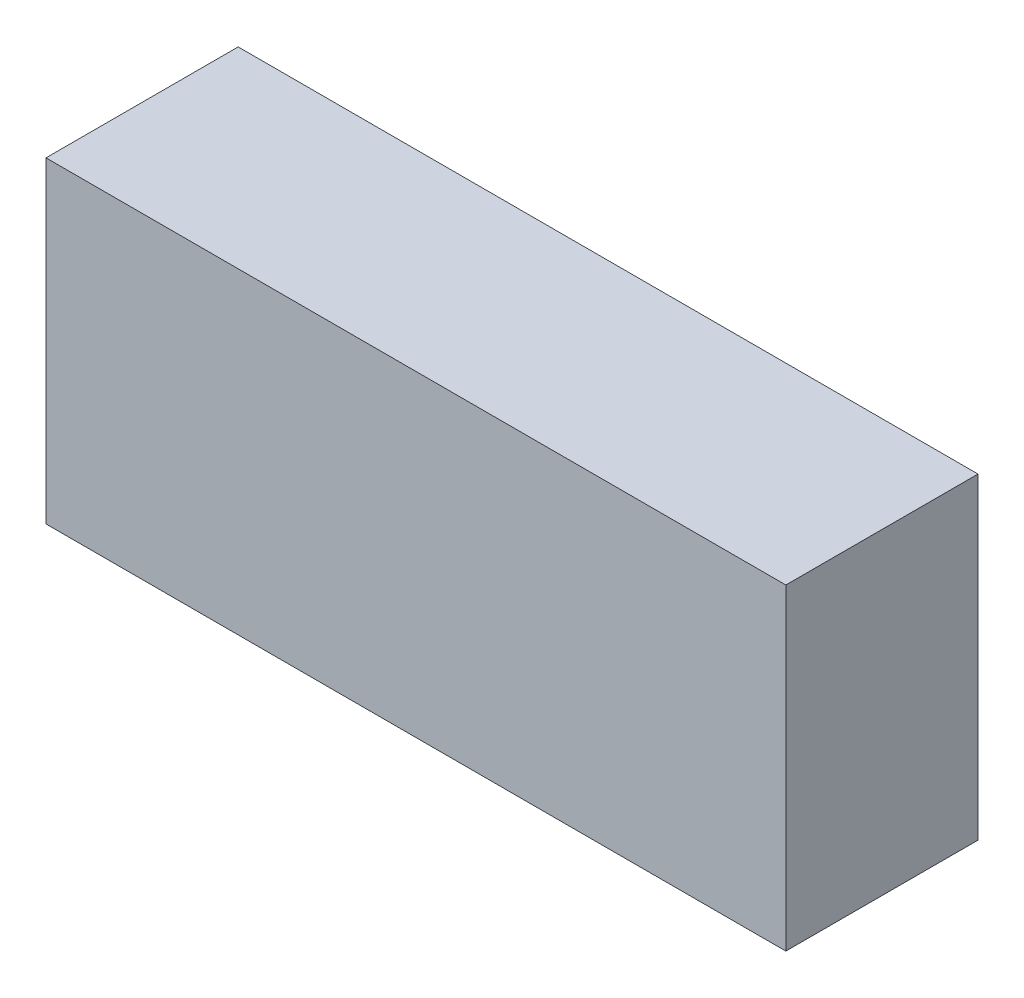
SolidWorks part; units mm, degrees
ref_plane "Plan de face" through (0, 0, 0) normal (0, 0, 1) x (1, 0, 0)
ref_plane "Plan de dessus" through (0, 0, 0) normal (0, 1, 0) x (1, 0, 0)
ref_plane "Plan de droite" through (0, 0, 0) normal (1, 0, 0) x (0, 0, -1)
sketch "Esquisse1" plane through (0, 0, 0) normal (0, 0, 1) x (1, 0, 0)
  line L1 (-36.9116, 17.8415) -> (40.0884, 17.8415)
  line L2 (-36.9116, 17.8415) -> (-36.9116, -15.1585)
  line L3 (-36.9116, -15.1585) -> (40.0884, -15.1585)
  line L4 (40.0884, 17.8415) -> (40.0884, -15.1585)
  dimension "D1" = 77
  dimension "D2" = 33
extrude "Boss.-Extru.1" add sketch "Esquisse1" along normal blind 20
